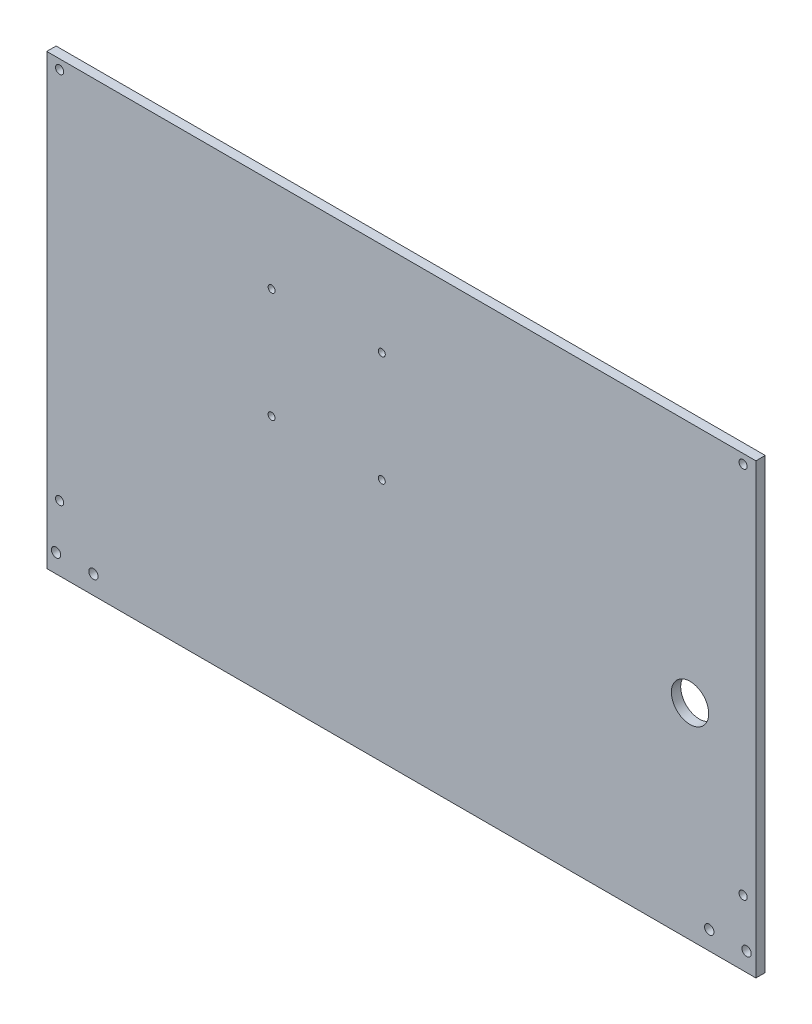
SolidWorks part; units mm, degrees
ref_plane "Front Plane" through (0, 0, 0) normal (0, 0, 1) x (1, 0, 0)
ref_plane "Top Plane" through (0, 0, 0) normal (0, 1, 0) x (1, 0, 0)
ref_plane "Right Plane" through (0, 0, 0) normal (1, 0, 0) x (0, 0, -1)
sketch "Sketch1" plane through (0, 0, 0) normal (0, 0, 1) x (1, 0, 0)
  line L1 (-241.3, -152.4) -> (241.3, -152.4)
  line L2 (-241.3, -152.4) -> (-241.3, 152.4)
  line L3 (-241.3, 152.4) -> (241.3, 152.4)
  line L4 (241.3, -152.4) -> (241.3, 152.4)
  line L5 (-241.3, -152.4) -> (241.3, 152.4) construction
  line L6 (-241.3, 152.4) -> (241.3, -152.4) construction
  point P0 (0, 0)
  dimension "D1" = 482.6
  dimension "D2" = 304.8
extrude "Boss-Extrude1" add sketch "Sketch1" along normal blind 6.35
sketch "Sketch2" plane through (0, 0, 6.35) normal (0, 0, 1) x (1, 0, 0)
  line L0 (-241.3, 0) -> (241.3, 0) construction
  line L1 (-241.3, 152.4) -> (-241.3, -152.4) construction
  line L2 (241.3, -152.4) -> (241.3, 152.4) construction
  line L3 (241.3, 152.4) -> (-241.3, 152.4) construction
  circle A0 centre (-232.5624, 146.05) radius 2.7813
  circle A1 centre (-232.5624, -107.95) radius 2.7813
  dimension "D2" = 5.5626
  dimension "D3" = 5.5626
  dimension "D1" = 8.7376
  dimension "D4" = 6.35
  dimension "D5" = 254
extrude "Cut-Extrude1" cut sketch "Sketch2" against normal through all
mirror "Mirror1" about plane through (0, 0, 0) normal (1, 0, 0) of "Cut-Extrude1"
sketch "Sketch3" plane through (0, 0, 6.35) normal (0, 0, 1) x (1, 0, 0)
  line L0 (-241.3, -139.7) -> (241.3, -139.7) construction
  line L1 (-241.3, 152.4) -> (-241.3, -152.4) construction
  line L2 (241.3, -152.4) -> (241.3, 152.4) construction
  line L3 (-241.3, -152.4) -> (241.3, -152.4) construction
  circle A0 centre (-234.95, -139.7) radius 3.175
  circle A1 centre (-209.55, -139.7) radius 3.175
  dimension "D2" = 6.35
  dimension "D3" = 6.35
  dimension "D4" = 25.4
  dimension "D5" = 6.35
  dimension "D1" = 12.7
extrude "Cut-Extrude2" cut sketch "Sketch3" against normal through all
mirror "Mirror2" about plane through (0, 0, 0) normal (1, 0, 0) of "Cut-Extrude2"
sketch "Sketch4" plane through (0, 0, 6.35) normal (0, 0, 1) x (1, 0, 0)
  line L0 (241.3, 152.4) -> (-241.3, 152.4) construction
  circle A0 centre (196.469, -12.7) radius 12.7
  dimension "D2" = 25.4
  dimension "D1" = 196.469
  dimension "D3" = 165.1
extrude "Cut-Extrude3" cut sketch "Sketch4" against normal through all
sketch "Sketch5" plane through (0, 0, 6.35) normal (0, 0, 1) x (1, 0, 0)
  line L0 (241.3, 152.4) -> (-241.3, 152.4) construction
  line L1 (-88.3, 13.9) -> (-13.3, 13.9) construction
  line L2 (-88.3, 13.9) -> (-88.3, 88.9) construction
  line L3 (-88.3, 88.9) -> (-13.3, 88.9) construction
  line L4 (-13.3, 13.9) -> (-13.3, 88.9) construction
  line L5 (-88.3, 13.9) -> (-13.3, 88.9) construction
  line L6 (-88.3, 88.9) -> (-13.3, 13.9) construction
  circle A0 centre (-88.3, 88.9) radius 2.3749
  circle A1 centre (-13.3, 88.9) radius 2.3749
  circle A2 centre (-13.3, 13.9) radius 2.3749
  circle A3 centre (-88.3, 13.9) radius 2.3749
  point P0 (-50.8, 51.4)
  point P8 (0, 0)
  point P13 (-41.5293, 51.4)
  dimension "D4" = 4.7498
  dimension "D5" = 4.7498
  dimension "D6" = 4.7498
  dimension "D7" = 4.7498
  dimension "D1" = 75
  dimension "D2" = 75
  dimension "D3" = 63.5
  dimension "D8" = 50.8
extrude "Cut-Extrude4" cut sketch "Sketch5" against normal through all
